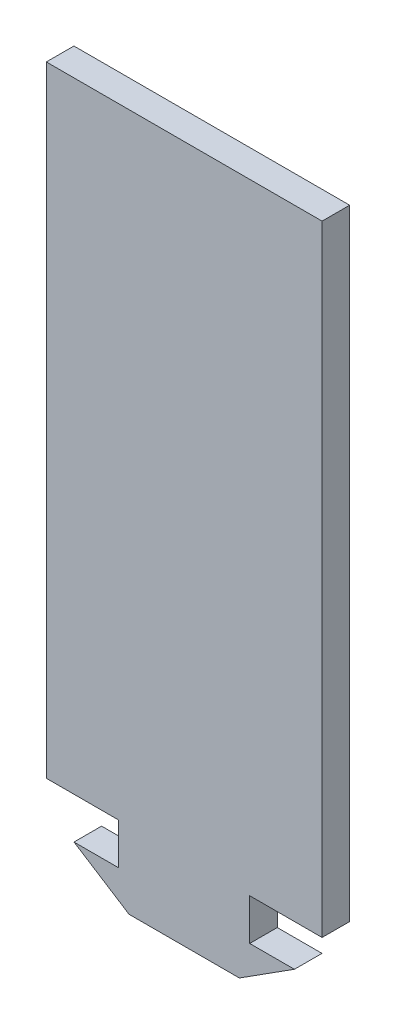
SolidWorks part; units mm, degrees
material "Акрил (Средняя-высокая ударопрочность)"
ref_plane "Спереди" through (0, 0, 0) normal (0, 0, 1) x (1, 0, 0)
ref_plane "Сверху" through (0, 0, 0) normal (0, 1, 0) x (1, 0, 0)
ref_plane "Справа" through (0, 0, 0) normal (1, 0, 0) x (0, 0, -1)
other "Configuration Table"
sketch "Эскиз1" plane through (0, 0, 0) normal (0, 0, 1) x (1, 0, 0)
  line L0 (-4.75, -25.5) -> (-7.9941, -25.5)
  line L1 (10, -22.5) -> (4.75, -22.5)
  line L2 (10, -22.5) -> (10, 22.5)
  line L3 (10, 22.5) -> (-10, 22.5)
  line L4 (-10, -22.5) -> (-10, 22.5)
  line L5 (10, -22.5) -> (-10, 22.5) construction
  line L6 (10, 22.5) -> (-10, -22.5) construction
  line L8 (-4.75, -25.5) -> (-4.75, -22.5)
  line L10 (4.75, -25.5) -> (4.75, -22.5)
  line L11 (-4.75, -25.5) -> (4.75, -22.5) construction
  line L12 (-4.75, -22.5) -> (4.75, -25.5) construction
  line L16 (-4.75, -22.5) -> (-10, -22.5)
  line L18 (4.75, -25.5) -> (7.9941, -25.5)
  line L19 (-7.9941, -25.5) -> (-4, -28.0439)
  line L20 (-4, -28.0439) -> (4, -28.0439)
  line L21 (4, -28.0439) -> (7.9941, -25.5)
  point P0 (0, 0)
  point P5 (0, -24)
  point P11 (0, 0)
  point P16 (0, 0)
  dimension "D1" = 9.5
  dimension "D2" = 45
  dimension "D3" = 20
  dimension "D4" = 8
  dimension "D5" = 9.5
  dimension "D6" = 2.0059
  dimension "D7" = 3
  dimension "D8" = 4.7355
extrude "Бобышка-Вытянуть1" add sketch "Эскиз1" along normal blind 2
